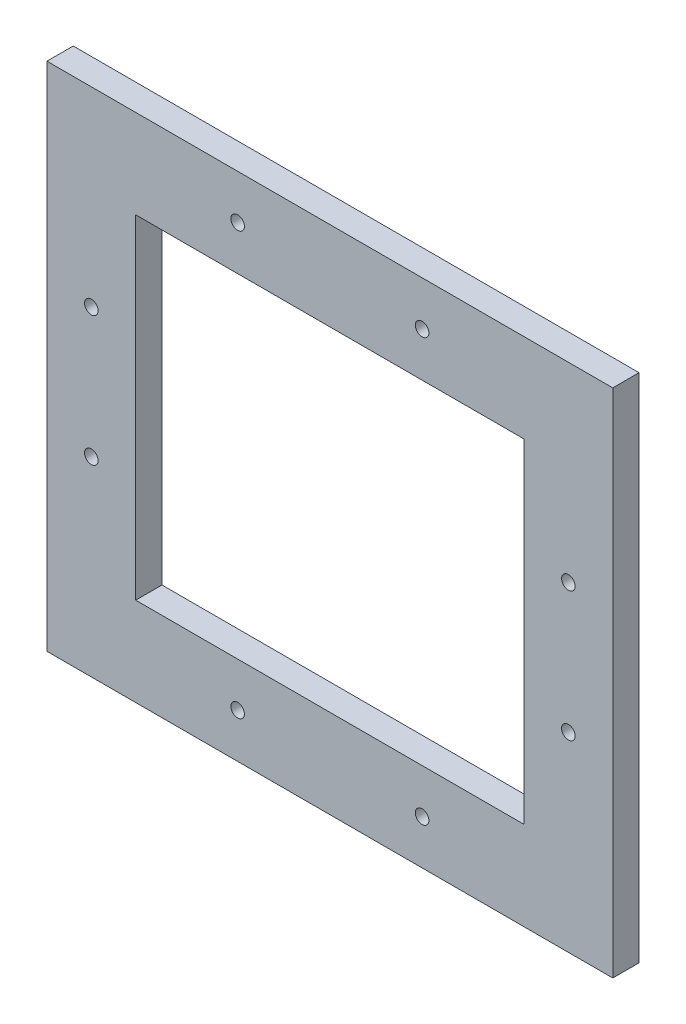
SolidWorks part; units mm, degrees
ref_plane "Спереди" through (0, 0, 0) normal (0, 0, 1) x (1, 0, 0)
ref_plane "Сверху" through (0, 0, 0) normal (0, 1, 0) x (1, 0, 0)
ref_plane "Справа" through (0, 0, 0) normal (1, 0, 0) x (0, 0, -1)
sketch "Эскиз1" plane through (0, 0, 0) normal (0, 0, 1) x (1, 0, 0)
  line L0 (-36.3383, 8.2203) -> (52.3117, 8.2203)
  line L1 (-56.5983, 28.4603) -> (72.5717, 28.4603)
  line L2 (-56.5983, 28.4603) -> (-56.5983, -88.2097)
  line L3 (-56.5983, -88.2097) -> (72.5717, -88.2097)
  line L4 (72.5717, 28.4603) -> (72.5717, -88.2097)
  line L5 (52.3117, 8.2203) -> (52.3117, -67.9697)
  line L6 (52.3117, -67.9697) -> (-36.3383, -67.9697)
  line L7 (-36.3383, -67.9697) -> (-36.3383, 8.2203)
  dimension "D1" = 129.17
  dimension "D2" = 116.67
  dimension "D3" = 20.26
  dimension "D4" = 20.24
  dimension "D5" = 20.24
  dimension "D6" = 20.26
extrude "Бобышка-Вытянуть1" add sketch "Эскиз1" along normal blind 6
sketch "Эскиз2" plane through (0, 0, 0) normal (0, 0, -1) x (-1, 0, 0)
  circle A0 centre (46.4641, -15.0688) radius 1.55
  circle A1 centre (46.4641, -44.6793) radius 1.55
  circle A2 centre (13.0691, -78.0743) radius 1.55
  circle A3 centre (-29.0413, -78.0743) radius 1.55
  circle A4 centre (-62.4364, -44.6793) radius 1.55
  circle A5 centre (-62.4364, -15.0688) radius 1.55
  circle A6 centre (-29.0413, 18.3262) radius 1.55
  circle A7 centre (13.0691, 18.3262) radius 1.55
extrude "Вырез-Вытянуть1" cut sketch "Эскиз2" against normal through all
